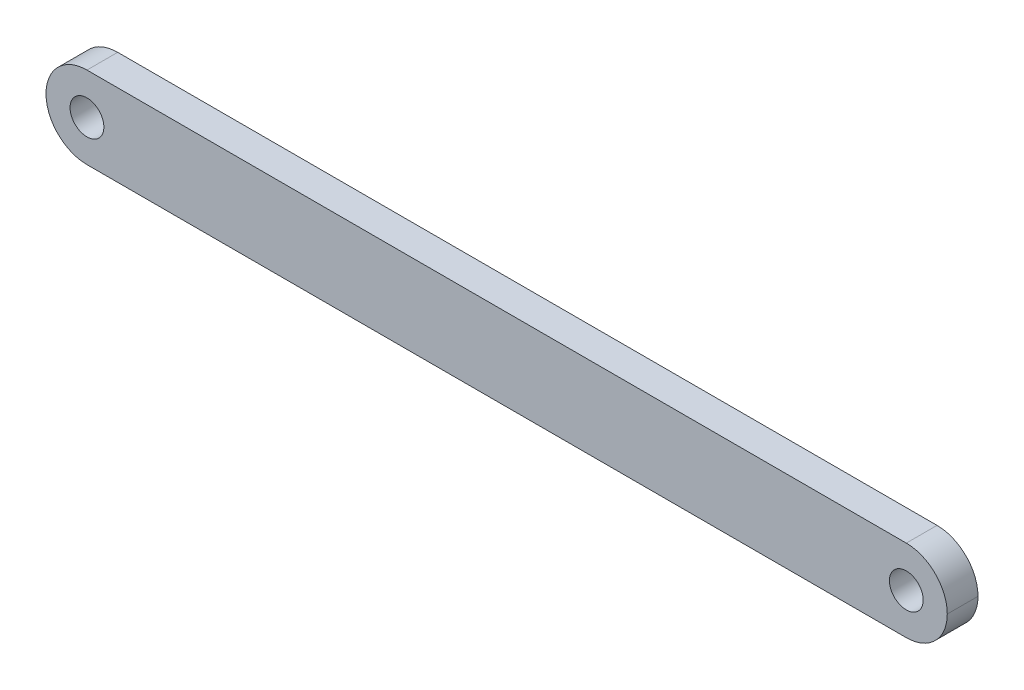
SolidWorks part; units mm, degrees
ref_plane "前视基准面" through (0, 0, 0) normal (0, 0, 1) x (1, 0, 0)
ref_plane "上视基准面" through (0, 0, 0) normal (0, 1, 0) x (1, 0, 0)
ref_plane "右视基准面" through (0, 0, 0) normal (1, 0, 0) x (0, 0, -1)
ref_plane "基准面4" through (0, 0, 0) normal (0, 0, -1) x (-1, 0, 0)
sketch "草图1" plane through (0, 0, 0) normal (0, 0, -1) x (-1, 0, 0)
  line L0 (-55.8602, 0) -> (24.1383, 0)
  line L1 (24.1383, 7.999) -> (-55.8602, 7.999)
  arc A0 (-55.8602, 7.999) -> (-59.8602, 4) centre (-55.8602, 3.999) ccw
  arc A1 (-59.8602, 4) -> (-55.8602, 0) centre (-55.8602, 4) ccw
  arc A2 (24.1383, 0) -> (28.1383, 3.999) centre (24.1383, 4) ccw
  arc A3 (28.1383, 3.999) -> (24.1383, 7.999) centre (24.1383, 3.999) ccw
  circle A4 centre (24.1388, 3.9985) radius 1.65
  circle A5 centre (-55.8597, 3.9995) radius 1.65
extrude "凸台-拉伸1" add sketch "草图1" against normal blind 3
sketch "草图2" plane through (0, 0, 0) normal (0, 0, -1) x (-1, 0, 0)
  text T0 "8"
extrude "切除-拉伸1" cut sketch "草图2" against normal blind 1
